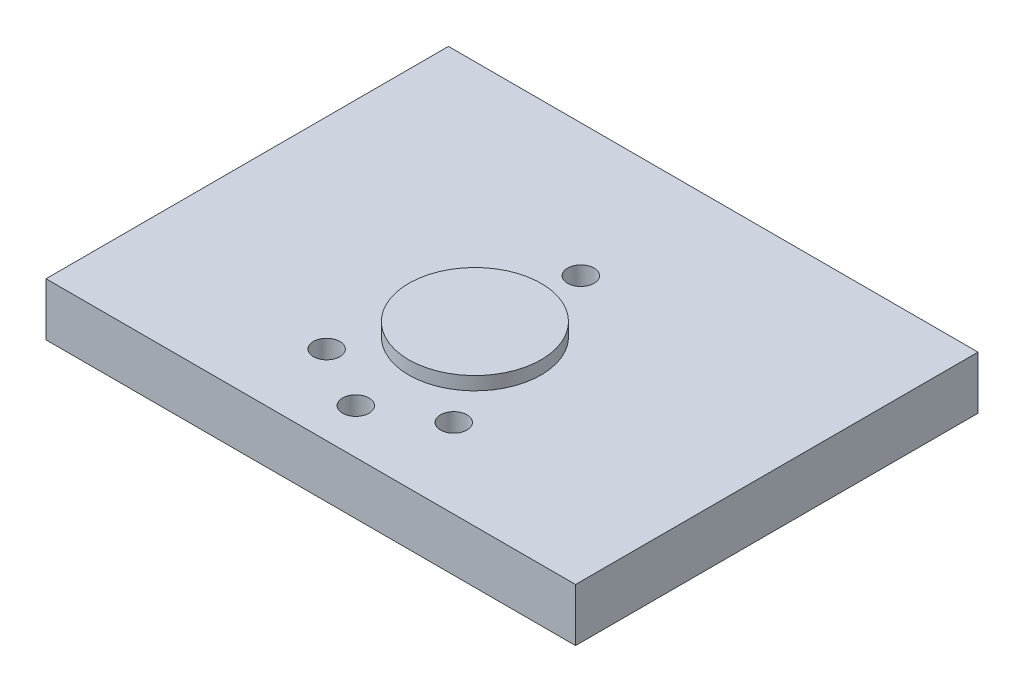
SolidWorks part; units mm, degrees
ref_plane "Front Plane" through (0, 0, 0) normal (0, 0, 1) x (1, 0, 0)
ref_plane "Top Plane" through (0, 0, 0) normal (0, 1, 0) x (1, 0, 0)
ref_plane "Right Plane" through (0, 0, 0) normal (1, 0, 0) x (0, 0, -1)
sketch "Sketch1" plane through (0, 0, 0) normal (0, 1, 0) x (1, 0, 0)
  line L1 (-63.5, 48.26) -> (63.5, 48.26)
  line L2 (-63.5, 48.26) -> (-63.5, -48.26)
  line L3 (-63.5, -48.26) -> (63.5, -48.26)
  line L4 (63.5, 48.26) -> (63.5, -48.26)
  line L5 (-63.5, 48.26) -> (63.5, -48.26) construction
  line L6 (-63.5, -48.26) -> (63.5, 48.26) construction
  point P0 (0, 0)
  dimension "D1" = 96.52
  dimension "D2" = 127
extrude "Boss-Extrude1" add sketch "Sketch1" along normal blind 15.875
sketch "Sketch2" plane through (0, 15.875, 0) normal (0, 1, 0) x (1, 0, 0)
  line L7 (63.5, -48.26) -> (63.5, 48.26)
  line L8 (63.5, 48.26) -> (-63.5, 48.26)
  line L9 (-63.5, 48.26) -> (-63.5, -48.26)
  line L10 (-63.5, -48.26) -> (63.5, -48.26)
  line L11 (63.5, -48.26) -> (63.5, 48.26)
  line L12 (63.5, 48.26) -> (-63.5, 48.26)
  line L13 (-63.5, 48.26) -> (-63.5, -48.26)
  line L14 (-63.5, -48.26) -> (63.5, -48.26)
  circle A0 centre (0, -8.89) radius 15.875
  dimension "D2" = 31.75
  dimension "D1" = 63.5
  dimension "D4" = 57.15
  dimension "D3" = 0
extrude "Cut-Extrude1" cut sketch "Sketch2" against normal blind 3.175
sketch "Sketch3" plane through (0, 12.7, 0) normal (0, 1, 0) x (1, 0, 0)
  line L0 (0, -8.89) -> (0, -48.26) construction
  line L1 (-63.5, -48.26) -> (63.5, -48.26) construction
  line L2 (0, -8.89) -> (0, 16.51) construction
  line L3 (0, -8.89) -> (15.24, -29.21) construction
  line L4 (0, -8.89) -> (-15.24, -29.21) construction
  point P5 (0, -37.465)
hole_wizard "1/4 (0.25) Diameter Hole1" positions "Sketch5" profile "Sketch6" hole size "1/4" standard "ANSI Inch" end condition up to next
sketch "Sketch5" plane through (0, 12.7, 0) normal (0, 1, 0) x (1, 0, 0)
  point P0 (15.24, -29.21)
  point P3 (0, -37.465)
  point P9 (0, 16.51)
  point P14 (-15.24, -29.21)
sketch "Sketch6" plane through (15.24, 12.7, 29.21) normal (1, 0, 0) x (0, 0, 1)
  line L0 (0, 0) -> (0, 12.7)
  line L1 (0, 12.7) -> (3.175, 12.7)
  line L2 (3.175, 12.7) -> (3.175, 0)
  line L5 (3.175, 0) -> (0, 0)
  line L11 (0, -6.35) -> (0, 107.95) construction
  dimension "Thru Hole Dia." = 6.35
  dimension "Thru Hole Depth" = 12.7
